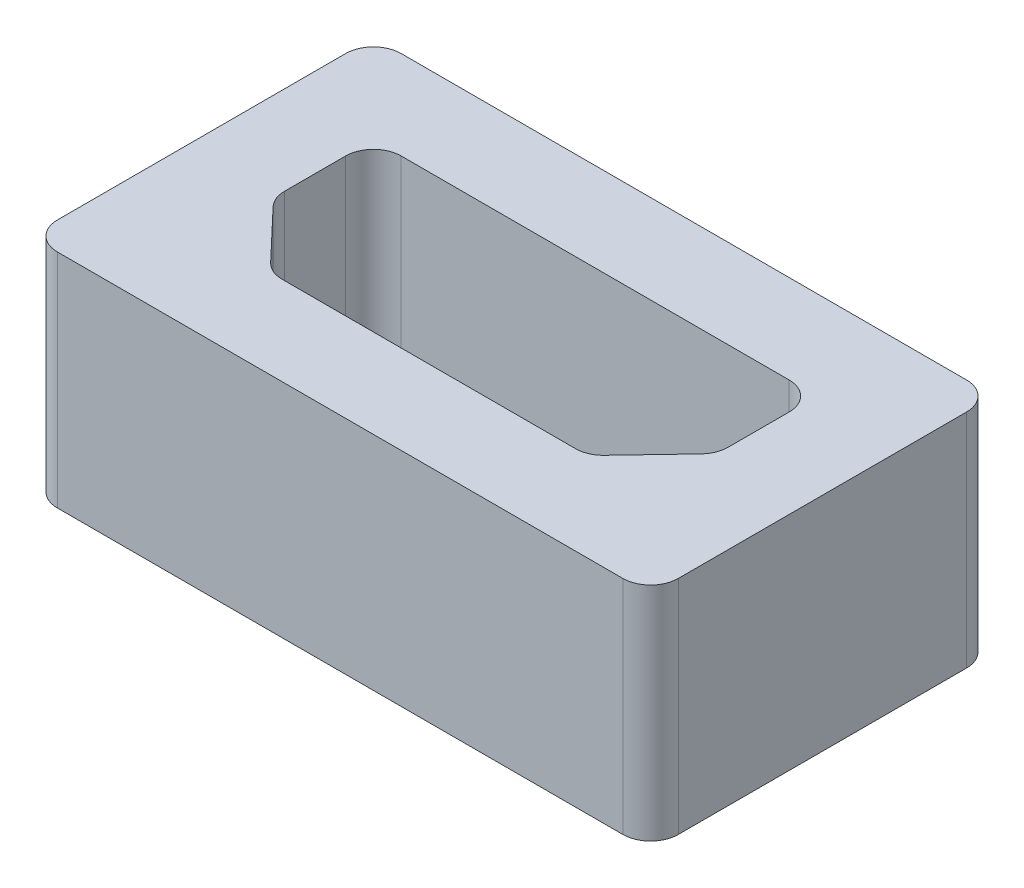
SolidWorks part; units mm, degrees
ref_plane "Спереди" through (0, 0, 0) normal (0, 0, 1) x (1, 0, 0)
ref_plane "Сверху" through (0, 0, 0) normal (0, 1, 0) x (1, 0, 0)
ref_plane "Справа" through (0, 0, 0) normal (1, 0, 0) x (0, 0, -1)
sketch "Эскиз1" plane through (0, 0, 0) normal (0, 1, 0) x (1, 0, 0)
  line L0 (-1.6, 4.6) -> (9.6, 4.6)
  line L1 (0, 0) -> (8, 0)
  line L2 (0, 0) -> (0, 3)
  line L3 (0, 3) -> (8, 3)
  line L4 (8, 0) -> (8, 3)
  line L5 (9.6, -1.6) -> (9.6, 4.6)
  line L6 (-1.6, -1.6) -> (9.6, -1.6)
  line L7 (-1.6, -1.6) -> (-1.6, 4.6)
  line L8 (1.1385, 0) -> (0, 1.1979)
  line L9 (4, 4.6) -> (4, -1.6) construction
  line L10 (6.8615, 0) -> (8, 1.1979)
  point P15 (8, 1.1979)
  point P16 (6.8615, 0)
  point P17 (0, 0)
  dimension "D2" = 8
  dimension "D3" = 3
  dimension "D1" = 1.6
extrude "Бобышка-Вытянуть1" add sketch "Эскиз1" along normal blind 4 contours L7 L6 L5 L0 L4 L1 L2 L3 | L9 L0 L7 L6 L1 L2 L3 | L1 L8 L2 | L10 L1 L4
sketch "Эскиз2" plane through (0, 0, 0) normal (0, -1, 0) x (1, 0, 0)
  line L4 (-1.6, -4.6) -> (9.6, -4.6)
  line L5 (9.6, -4.6) -> (9.6, 1.6)
  line L6 (9.6, 1.6) -> (-1.6, 1.6)
  line L7 (-1.6, 1.6) -> (-1.6, -4.6)
  line L8 (-1.6, -4.6) -> (9.6, -4.6)
  line L9 (9.6, -4.6) -> (9.6, 1.6)
  line L10 (9.6, 1.6) -> (-1.6, 1.6)
  line L11 (-1.6, 1.6) -> (-1.6, -4.6)
  dimension "D1" = 0
fillet "Скругление1" radius 0.5 2 edges at (0, 2, -3) (8, 2, -3)
fillet "Скругление2" radius 0.5 8 edges at (-1.6, 2, 1.6) (-1.6, 2, -4.6) (9.6, 2, 1.6) (9.6, 2, -4.6) (1.1385, 2, 0) (0, 2, -1.1979) (8, 2, -1.1979) (6.8615, 2, 0)
